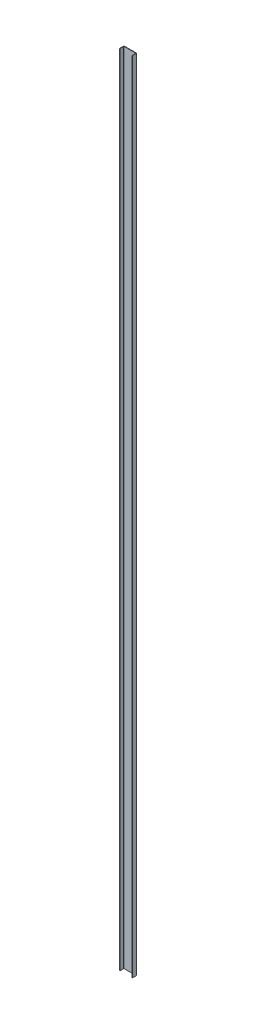
SolidWorks part; units mm, degrees
ref_plane "Front Plane" through (0, 0, 0) normal (0, 0, 1) x (1, 0, 0)
ref_plane "Top Plane" through (0, 0, 0) normal (0, 1, 0) x (1, 0, 0)
ref_plane "Right Plane" through (0, 0, 0) normal (1, 0, 0) x (0, 0, -1)
sketch "Sketch1" plane through (0, 0, 0) normal (0, 1, 0) x (1, 0, 0)
  line L0 (0, 0) -> (0, 10)
  line L1 (0, 10) -> (30, 10)
  line L2 (30, 10) -> (30, 0)
  line L3 (0, 0) -> (30, 0) construction
  line L4 (-1, 0) -> (-1, 11)
  line L5 (-1, 11) -> (31, 11)
  line L6 (31, 11) -> (31, 0)
  line L7 (30, 0) -> (31, 0)
  line L8 (0, 0) -> (-1, 0)
  dimension "D1" = 30
  dimension "D2" = 10
  dimension "D3" = 1
extrude "Boss-Extrude1" add sketch "Sketch1" along normal blind 2000
fillet "Fillet1" radius 1 4 edges at (30, 1000, -10) (0, 1000, -10) (31, 1000, -11) (-1, 1000, -11)
